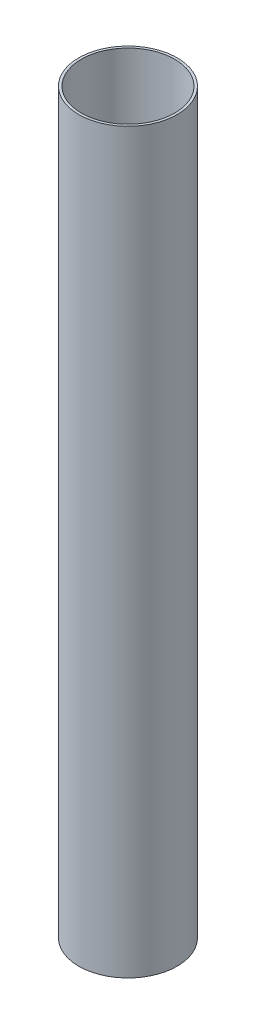
SolidWorks part; units mm, degrees
ref_plane "Front Plane" through (0, 0, 0) normal (0, 0, 1) x (1, 0, 0)
ref_plane "Top Plane" through (0, 0, 0) normal (0, 1, 0) x (1, 0, 0)
ref_plane "Right Plane" through (0, 0, 0) normal (1, 0, 0) x (0, 0, -1)
sketch "Sketch1" plane through (0, 0, 0) normal (0, 1, 0) x (1, 0, 0)
  circle A0 centre (0, 0) radius 38
  circle A1 centre (0, 0) radius 40
  dimension "D1" = 80
  dimension "D2" = 2
extrude "Boss-Extrude1" add sketch "Sketch1" along normal blind 600
